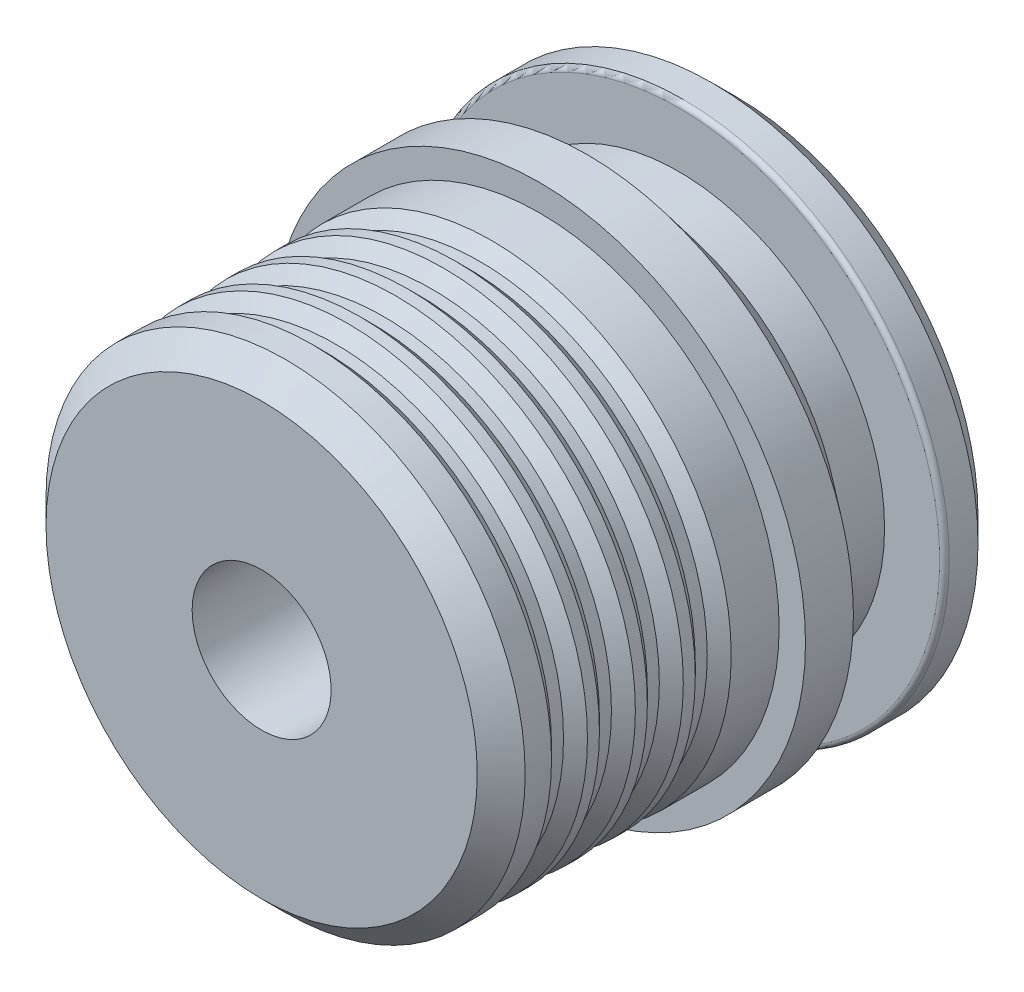
SolidWorks part; units mm, degrees
ref_plane "정면" through (0, 0, 0) normal (0, 0, 1) x (1, 0, 0)
ref_plane "윗면" through (0, 0, 0) normal (0, 1, 0) x (1, 0, 0)
ref_plane "우측면" through (0, 0, 0) normal (1, 0, 0) x (0, 0, -1)
sketch "스케치3" plane through (0, 0, 0) normal (0, 1, 0) x (1, 0, 0)
  line L0 (0, 0) -> (0, -21.8) construction
  line L1 (11.1, 0) -> (11.1, -2.4)
  line L2 (11.1, -2.4) -> (8.6, -2.4)
  line L3 (11.1, 0) -> (6.25, 0)
  line L4 (8.6, -2.4) -> (8.6, -4.2)
  line L5 (8.6, -4.2) -> (11.1, -6.2)
  line L6 (11.1, -6.2) -> (11.1, -8.2)
  line L7 (11.1, -8.2) -> (10, -8.2)
  line L8 (10, -8.2) -> (10, -10.2)
  line L9 (10, -10.2) -> (9.5, -10.7)
  line L10 (9.5, -10.7) -> (9.5, -11.2)
  line L12 (10, -19.8) -> (2.9, -19.8)
  line L13 (2.9, -19.8) -> (2.9, -11.8)
  line L14 (2.9, -11.8) -> (4.4, -11.8)
  line L15 (4.4, -11.8) -> (4.4, -10)
  line L16 (4.4, -10) -> (3.4, -10)
  line L17 (3.4, -10) -> (3.4, -8.5)
  line L18 (3.4, -8.5) -> (6.25, -7.7363)
  line L19 (6.25, -7.7363) -> (6.25, 0)
  line L20 (0, 0) -> (6.25, 0) construction
  line L21 (9.5, -11.2) -> (10, -11.7)
  line L22 (9.5, -13.2) -> (10, -13.7)
  line L23 (9.5, -12.7) -> (9.5, -13.2)
  line L24 (10, -12.2) -> (9.5, -12.7)
  line L25 (9.5, -15.2) -> (10, -15.7)
  line L26 (9.5, -14.7) -> (9.5, -15.2)
  line L27 (10, -14.2) -> (9.5, -14.7)
  line L28 (9.5, -17.2) -> (10, -17.7)
  line L29 (9.5, -16.7) -> (9.5, -17.2)
  line L30 (10, -16.2) -> (9.5, -16.7)
  line L34 (10, -11.7) -> (10, -12.2)
  line L35 (10, -13.7) -> (10, -14.2)
  line L36 (10, -15.7) -> (10, -16.2)
  line L37 (10, -17.7) -> (10, -19.8)
  line L39 (9.5, -18.7) -> (9.5, -19.2) [skipped]
  line L40 (9.75, -19.45) -> (9.85, -19.55) [skipped]
  line L41 (10, -18.2) -> (9.5, -18.7) [skipped]
  dimension "D2" = 0.5
  dimension "D3" = 2.4
  dimension "D4" = 2
  dimension "D5" = 1.8
  dimension "D6" = 2
  dimension "D7" = 12.5
  dimension "D8" = 5.8
  dimension "D9" = 20
  dimension "D10" = 17.2
  dimension "D11" = 8
  dimension "D12" = 1.5
  dimension "D13" = 10
  dimension "D14" = 8.8
  dimension "D15" = 6.8
  dimension "D16" = 105
  dimension "D17" = 1.8
  dimension "D18" = 1.5
  dimension "D19" = 22.2
  dimension "D20" = 0.5
  dimension "D21" = 2
  dimension "D22" = 5
revolve "회전2" add sketch "스케치3" angle 360 about L0
chamfer "모따기1" distance 1 angle 45 2 edges at (-6.25, 0, 0) (-10, 0, 19.8)
chamfer "모따기2" distance 1 angle 45 1 edges at (-11.1, 0, 0)
fillet "필렛1" radius 0.2 1 edges at (-11.1, 0, 2.4)
